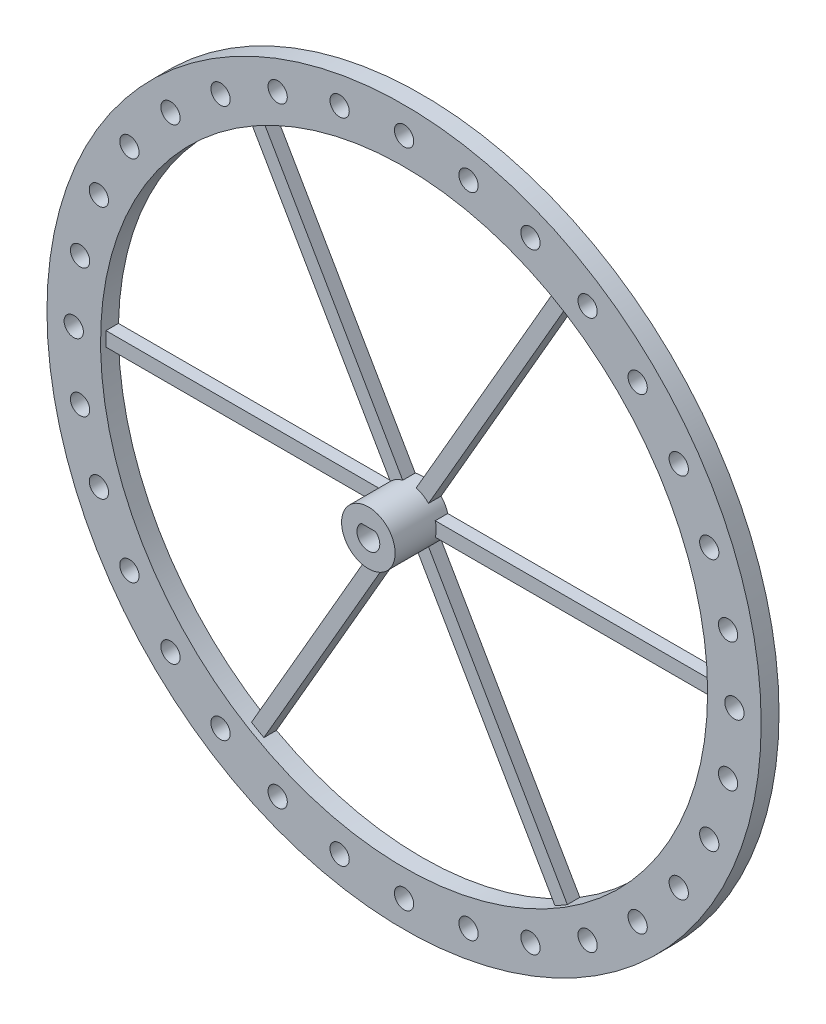
SolidWorks part; units mm, degrees
ref_plane "Front Plane" through (0, 0, 0) normal (0, 0, 1) x (1, 0, 0)
ref_plane "Top Plane" through (0, 0, 0) normal (0, 1, 0) x (1, 0, 0)
ref_plane "Right Plane" through (0, 0, 0) normal (1, 0, 0) x (0, 0, -1)
sketch "Sketch1" plane through (0, 0, 0) normal (0, 0, 1) x (1, 0, 0)
  line L0 (-85, 0) -> (-100, 0)
  line L1 (0, 85) -> (0, 100)
  line L2 (85, 0) -> (100, 0)
  line L3 (0, -85) -> (0, -100)
  circle A0 centre (0, 0) radius 100
  circle A1 centre (0, 0) radius 85
  circle A2 centre (0, 0) radius 92.5 construction
  circle A3 centre (-92.5, 0) radius 2.7
  circle A4 centre (-90.7226, 18.0459) radius 2.7
  circle A5 centre (-85.4589, 35.3982) radius 2.7
  circle A6 centre (-76.9109, 51.3902) radius 2.7
  circle A7 centre (-65.4074, 65.4074) radius 2.7
  circle A8 centre (-51.3902, 76.9109) radius 2.7
  circle A9 centre (-35.3982, 85.4589) radius 2.7
  circle A10 centre (-18.0459, 90.7226) radius 2.7
  circle A11 centre (0, 92.5) radius 2.7
  circle A12 centre (18.0459, 90.7226) radius 2.7
  circle A13 centre (35.3982, 85.4589) radius 2.7
  circle A14 centre (51.3902, 76.9109) radius 2.7
  circle A15 centre (65.4074, 65.4074) radius 2.7
  circle A16 centre (76.9109, 51.3902) radius 2.7
  circle A17 centre (85.4589, 35.3982) radius 2.7
  circle A18 centre (90.7226, 18.0459) radius 2.7
  circle A19 centre (92.5, 0) radius 2.7
  circle A20 centre (90.7226, -18.0459) radius 2.7
  circle A21 centre (85.4589, -35.3982) radius 2.7
  circle A22 centre (76.9109, -51.3902) radius 2.7
  circle A23 centre (65.4074, -65.4074) radius 2.7
  circle A24 centre (51.3902, -76.9109) radius 2.7
  circle A25 centre (35.3982, -85.4589) radius 2.7
  circle A26 centre (18.0459, -90.7226) radius 2.7
  circle A27 centre (0, -92.5) radius 2.7
  circle A28 centre (-18.0459, -90.7226) radius 2.7
  circle A29 centre (-35.3982, -85.4589) radius 2.7
  circle A30 centre (-51.3902, -76.9109) radius 2.7
  circle A31 centre (-65.4074, -65.4074) radius 2.7
  circle A32 centre (-76.9109, -51.3902) radius 2.7
  circle A33 centre (-85.4589, -35.3982) radius 2.7
  circle A34 centre (-90.7226, -18.0459) radius 2.7
  point P80 (0, 0)
  dimension "D1" = 200
  dimension "D2" = 15
  dimension "D3" = 7.5
  dimension "D4" = 5.4
  dimension "D5" = 32
extrude "Boss-Extrude1" add sketch "Sketch1" along normal blind 5 contours A19 L2 A0 L1 A11 A1 A18 A17 A16 A15 A14 A13 A12 | A27 L3 A0 L2 A19 A1 A26 A25 A24 A23 A22 A21 A20 | A27 L3 A1 L0 A3 A0 A34 A33 A32 A31 A30 A29 A28 | A11 L1 A0 L0 A3 A1 A10 A9 A8 A7 A6 A5 A4
sketch "Sketch2" plane through (0, 0, 0) normal (0, 0, 1) x (1, 0, 0)
  line L0 (-1.9975, 2.5) -> (1.9975, 2.5)
  circle A0 centre (0, 0) radius 7.5
  arc A1 (-1.9975, 2.5) -> (1.9975, 2.5) centre (0, 0) ccw
  dimension "D1" = 15
  dimension "D2" = 6.4
  dimension "D3" = 2.5
extrude "Boss-Extrude2" add sketch "Sketch2" along normal blind 15 separate body
sketch "Sketch3" plane through (0, 0, 0) normal (0, 0, 1) x (1, 0, 0)
  line L0 (7.5, 0) -> (85, 0) construction
  line L1 (84.9765, 2) -> (7.2284, 2)
  line L2 (84.9765, -2) -> (7.2284, -2)
  line L3 (44.2203, -72.5918) -> (5.3463, -5.26)
  line L4 (40.7562, -74.5918) -> (1.8822, -7.26)
  line L5 (-40.7562, -74.5918) -> (-1.8822, -7.26)
  line L6 (-44.2203, -72.5918) -> (-5.3463, -5.26)
  line L7 (-84.9765, -2) -> (-7.2284, -2)
  line L8 (-84.9765, 2) -> (-7.2284, 2)
  line L9 (-44.2203, 72.5918) -> (-5.3463, 5.26)
  line L10 (-40.7562, 74.5918) -> (-1.8822, 7.26)
  line L11 (40.7562, 74.5918) -> (1.8822, 7.26)
  line L12 (44.2203, 72.5918) -> (5.3463, 5.26)
  circle A0 centre (0, 0) radius 7.5 construction
  circle A1 centre (0, 0) radius 85 construction
  arc A2 (5.3463, 5.26) -> (1.8822, 7.26) centre (0, 0) ccw
  arc A3 (40.7562, -74.5918) -> (44.2203, -72.5918) centre (0, 0) ccw
  arc A4 (-1.8822, 7.26) -> (-5.3463, 5.26) centre (0, 0) ccw
  arc A5 (-7.2284, 2) -> (-7.2284, -2) centre (0, 0) ccw
  arc A6 (-5.3463, -5.26) -> (-1.8822, -7.26) centre (0, 0) ccw
  arc A7 (1.8822, -7.26) -> (5.3463, -5.26) centre (0, 0) ccw
  arc A8 (7.2284, -2) -> (7.2284, 2) centre (0, 0) ccw
  arc A9 (84.9765, -2) -> (84.9765, 2) centre (0, 0) ccw
  arc A10 (44.2203, 72.5918) -> (40.7562, 74.5918) centre (0, 0) ccw
  arc A11 (-40.7562, 74.5918) -> (-44.2203, 72.5918) centre (0, 0) ccw
  arc A12 (-84.9765, 2) -> (-84.9765, -2) centre (0, 0) ccw
  arc A13 (-44.2203, -72.5918) -> (-40.7562, -74.5918) centre (0, 0) ccw
  point P34 (0, 0)
  dimension "D1" = 2
  dimension "D2" = 2
  dimension "D3" = 6
extrude "Boss-Extrude3" add sketch "Sketch3" along normal blind 3.5
